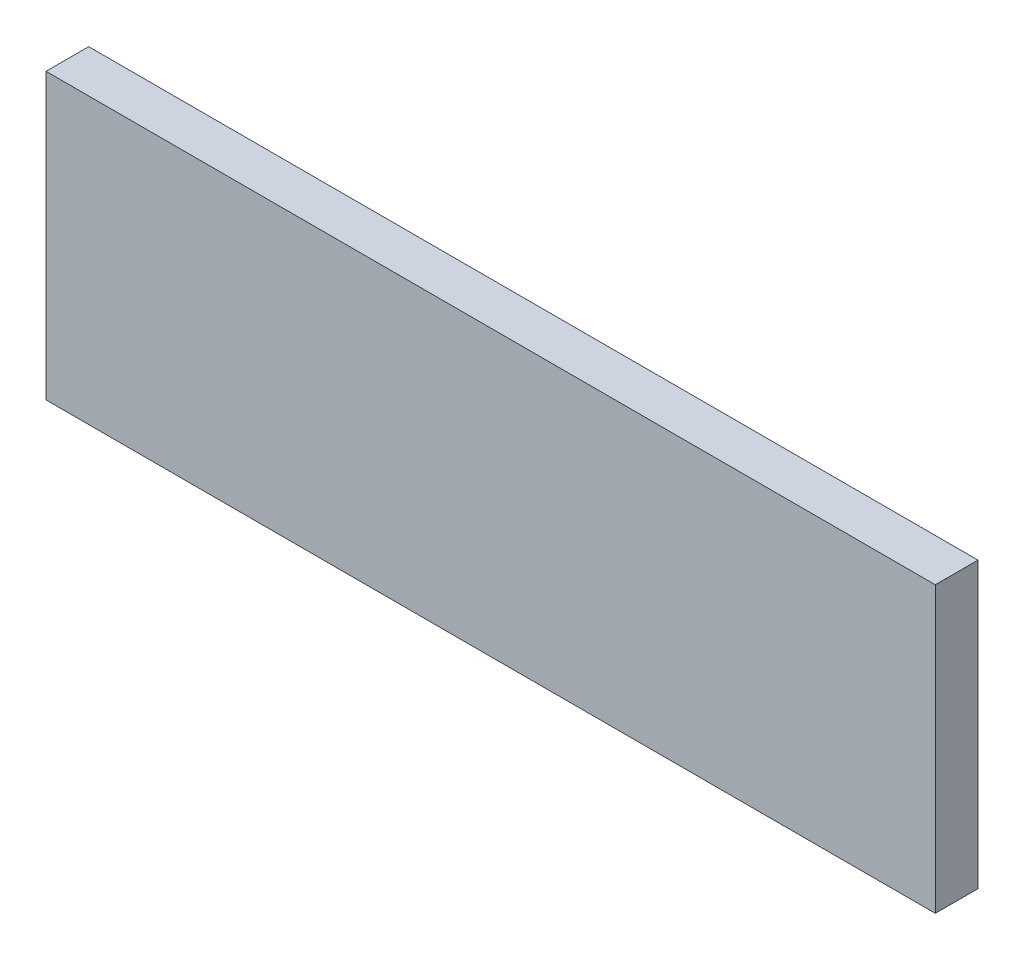
SolidWorks part; units mm, degrees
ref_plane "Alzado" through (0, 0, 0) normal (0, 0, 1) x (1, 0, 0)
ref_plane "Planta" through (0, 0, 0) normal (0, 1, 0) x (1, 0, 0)
ref_plane "Vista lateral" through (0, 0, 0) normal (1, 0, 0) x (0, 0, -1)
sketch "Croquis1" plane through (0, 0, 0) normal (0, 0, 1) x (1, 0, 0)
  line L1 (-23.6842, 5.9514) -> (1.3158, 5.9514)
  line L2 (-23.6842, 5.9514) -> (-23.6842, -2.0486)
  line L3 (-23.6842, -2.0486) -> (1.3158, -2.0486)
  line L4 (1.3158, 5.9514) -> (1.3158, -2.0486)
  dimension "D1" = 25
  dimension "D2" = 8
extrude "Saliente-Extruir1" add sketch "Croquis1" along normal blind 1.2
